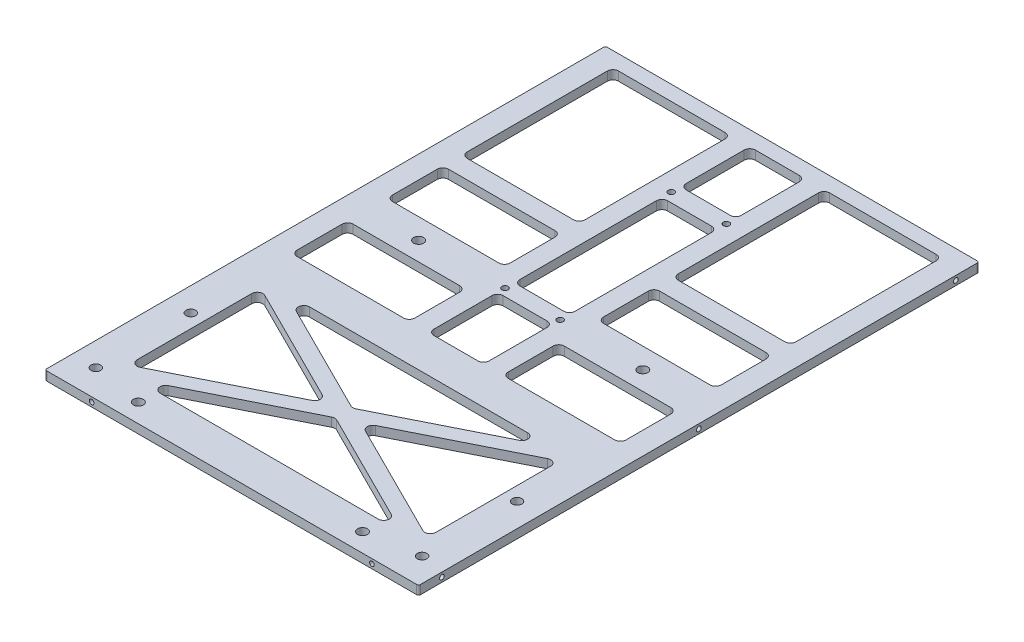
SolidWorks part; units mm, degrees
material "6061 Alloy"
ref_plane "Front Plane" through (0, 0, 0) normal (0, 0, 1) x (1, 0, 0)
ref_plane "Top Plane" through (0, 0, 0) normal (0, 1, 0) x (1, 0, 0)
ref_plane "Right Plane" through (0, 0, 0) normal (1, 0, 0) x (0, 0, -1)
sketch "Sketch1" plane through (0, 0, 0) normal (0, 1, 0) x (1, 0, 0)
  line L1 (-100, -150) -> (100, -150)
  line L2 (-100, -150) -> (-100, 150)
  line L3 (-100, 150) -> (100, 150)
  line L4 (100, -150) -> (100, 150)
  line L5 (-100, -150) -> (100, 150) construction
  line L6 (-100, 150) -> (100, -150) construction
  point P0 (0, 0)
  dimension "D1" = 300
  dimension "D2" = 200
extrude "Boss-Extrude1" add sketch "Sketch1" along normal blind 4.7625
sketch "Sketch2" plane through (0, 4.7625, 0) normal (0, 1, 0) x (1, 0, 0)
  line L0 (100, -150) -> (100, 150) construction
  line L1 (-100, -122.7) -> (100, -122.7) construction
  line L2 (-100, -122.7) -> (-100, -97.3) construction
  line L3 (-100, -97.3) -> (100, -97.3) construction
  line L4 (100, -122.7) -> (100, -97.3) construction
  line L5 (-100, -122.7) -> (100, -97.3) construction
  line L6 (-100, -97.3) -> (100, -122.7) construction
  line L7 (-100, -150) -> (100, -150) construction
  line L8 (100, 150) -> (-100, 150) construction
  line L9 (-100, -97.3) -> (-87.3, -97.3) construction
  line L10 (-100, -97.3) -> (-100, -84.6) construction
  line L11 (-100, -84.6) -> (-87.3, -84.6) construction
  line L12 (-87.3, -97.3) -> (-87.3, -84.6) construction
  line L13 (100, -97.3) -> (87.3, -97.3) construction
  line L14 (100, -97.3) -> (100, -84.6) construction
  line L15 (100, -84.6) -> (87.3, -84.6) construction
  line L16 (87.3, -97.3) -> (87.3, -84.6) construction
  line L17 (100, -122.7) -> (87.3, -122.7) construction
  line L18 (100, -122.7) -> (100, -135.4) construction
  line L19 (100, -135.4) -> (87.3, -135.4) construction
  line L20 (87.3, -122.7) -> (87.3, -135.4) construction
  line L21 (-100, -122.7) -> (-87.3, -122.7) construction
  line L22 (-100, -122.7) -> (-100, -135.4) construction
  line L23 (-100, -135.4) -> (-87.3, -135.4) construction
  line L24 (-87.3, -122.7) -> (-87.3, -135.4) construction
  line L25 (-100, -110) -> (100, -110) construction
  line L28 (-60, -140) -> (60, -140) construction
  line L29 (-60, -140) -> (-60, 10) construction
  line L30 (-60, 10) -> (60, 10) construction
  line L31 (60, -140) -> (60, 10) construction
  line L32 (-60, -140) -> (60, 10) construction
  line L33 (-60, 10) -> (60, -140) construction
  line L34 (-14.75, 11) -> (14.75, 11) construction
  line L35 (-14.75, 11) -> (-14.75, 100) construction
  line L36 (-14.75, 100) -> (14.75, 100) construction
  line L37 (14.75, 11) -> (14.75, 100) construction
  line L38 (-14.75, 11) -> (14.75, 100) construction
  line L39 (-14.75, 100) -> (14.75, 11) construction
  line L40 (-12.5, -79) -> (12.5, -79) construction
  line L41 (-12.5, -79) -> (-12.5, -4) construction
  line L42 (-12.5, -4) -> (12.5, -4) construction
  line L43 (12.5, -79) -> (12.5, -4) construction
  line L44 (-12.5, -79) -> (12.5, -4) construction
  line L45 (-12.5, -4) -> (12.5, -79) construction
  point P0 (0, -110)
  point P24 (0, 55.5)
  point P26 (0, -110)
  point P32 (0, -41.5)
  point P123 (0, -65)
  dimension "D1" = 25.4
  dimension "D2" = 40
  dimension "D3" = 12.7
  dimension "D4" = 12.7
  dimension "D5" = 120
  dimension "D6" = 150
  dimension "D7" = 10
  dimension "D8" = 75
  dimension "D9" = 89
  dimension "D10" = 29.5
  dimension "D11" = 50
  dimension "D12" = 25
  dimension "D13" = 15
hole_wizard "1/4-20 Tapped Hole1" positions "Sketch4" profile "Sketch5" tap size "1/4-20" standard "ANSI Inch" end condition through all
sketch "Sketch4" plane through (0, 4.7625, 0) normal (0, 1, 0) x (1, 0, 0)
  point P0 (-87.3, -84.6)
  point P3 (-87.3, -135.4)
  point P6 (87.3, -135.4)
  point P9 (87.3, -84.6)
sketch "Sketch5" plane through (-87.3, 4.7625, 84.6) normal (1, 0, 0) x (0, 0, 1)
  line L0 (0, 0) -> (0, 4.7625)
  line L1 (0, 4.7625) -> (2.5527, 4.7625)
  line L2 (2.5527, 4.7625) -> (2.5527, 0)
  line L5 (2.5527, 0) -> (0, 0)
  line L11 (0, -6.35) -> (0, 107.95) construction
  dimension "Thru Tap Drill Dia." = 5.1054
  dimension "Thru Tap Drill Depth" = 4.7625
ref_plane "Plane1" through (0, 0, 110) normal (0, 0, 1) x (1, 0, 0)
hole_wizard "M4x0.7 Tapped Hole1" positions "Sketch16" profile "Sketch17" tap size "M4x0.7" standard "ANSI Metric" end condition through all
sketch "Sketch16" plane through (0, 4.7625, 0) normal (0, 1, 0) x (1, 0, 0)
  point P12 (-14.75, 11)
  point P15 (14.75, 11)
  point P18 (14.75, 100)
  point P21 (-14.75, 100)
sketch "Sketch17" plane through (-14.75, 4.7625, -11) normal (1, 0, 0) x (0, 0, 1)
  line L0 (0, 0) -> (0, 4.7625)
  line L1 (0, 4.7625) -> (1.65, 4.7625)
  line L2 (1.65, 4.7625) -> (1.65, 0)
  line L5 (1.65, 0) -> (0, 0)
  line L11 (0, -6.35) -> (0, 107.95) construction
  dimension "Thru Tap Drill Dia." = 3.3
  dimension "Thru Tap Drill Depth" = 4.7625
cosmetic thread "Hole Thread1" parameters "D2"=4
cosmetic thread "Hole Thread2" parameters "D2"=4
cosmetic thread "Hole Thread3" parameters "D2"=4
cosmetic thread "Hole Thread4" parameters "D2"=4
hole_wizard "M5 Clearance Hole1" positions "Sketch7" profile "Sketch8" hole size "M5" standard "ANSI Metric" end condition through all
sketch "Sketch7" plane through (0, 4.7625, 0) normal (0, 1, 0) x (1, 0, 0)
  point P0 (-60, 10)
  point P3 (-60, -140)
  point P6 (60, -140)
  point P9 (60, 10)
sketch "Sketch8" plane through (-60, 4.7625, -10) normal (1, 0, 0) x (0, 0, 1)
  line L0 (0, 0) -> (0, 4.7625)
  line L1 (0, 4.7625) -> (2.65, 4.7625)
  line L2 (2.65, 4.7625) -> (2.65, 0)
  line L5 (2.65, 0) -> (0, 0)
  line L11 (0, -6.35) -> (0, 107.95) construction
  dimension "Thru Hole Dia." = 5.3
  dimension "Thru Hole Depth" = 4.7625
sketch "Sketch9" plane through (0, 4.7625, 0) normal (0, 1, 0) x (1, 0, 0)
  line L23 (-81.7889, -53.5777) -> (78.2111, -133.5777) construction
  line L24 (-80, -130) -> (80, -130) construction
  line L25 (-80, -130) -> (-80, -50) construction
  line L26 (-80, -50) -> (80, -50) construction
  line L27 (80, -130) -> (80, -50) construction
  line L28 (-80, -130) -> (80, -50) construction
  line L29 (-80, -50) -> (80, -130) construction
  line L30 (-78.2111, -46.4223) -> (81.7889, -126.4223) construction
  line L31 (-78.2111, -133.5777) -> (81.7889, -53.5777) construction
  line L32 (-81.7889, -126.4223) -> (78.2111, -46.4223) construction
  line L33 (-80, -54.4721) -> (-80, -125.5279)
  line L34 (-80, -125.5279) -> (-8.9443, -90)
  line L35 (-8.9443, -90) -> (-80, -54.4721)
  line L36 (-71.0557, -50) -> (71.0557, -50)
  line L37 (71.0557, -50) -> (0, -85.5279)
  line L38 (0, -85.5279) -> (-71.0557, -50)
  line L39 (80, -54.4721) -> (8.9443, -90)
  line L40 (8.9443, -90) -> (80, -125.5279)
  line L41 (80, -125.5279) -> (80, -54.4721)
  line L42 (-71.0557, -130) -> (0, -94.4721)
  line L43 (0, -94.4721) -> (71.0557, -130)
  line L44 (71.0557, -130) -> (-71.0557, -130)
  line L45 (-100, -150) -> (100, -150) construction
  line L47 (-88, -30) -> (-25, -30) construction
  line L48 (-88, -30) -> (-88, 142) construction
  line L49 (-88, 142) -> (-25, 142)
  line L50 (-25, -30) -> (-25, 142) construction
  line L51 (-88, -30) -> (-25, 142) construction
  line L52 (-88, 142) -> (-25, -30) construction
  line L54 (25, -30) -> (88, -30) construction
  line L55 (25, -30) -> (25, 142) construction
  line L56 (25, 142) -> (88, 142)
  line L57 (88, -30) -> (88, 142) construction
  line L58 (25, -30) -> (88, 142) construction
  line L59 (25, 142) -> (88, -30) construction
  line L60 (-56.5, 56) -> (56.5, 56) construction
  line L62 (100, 150) -> (-100, 150) construction
  line L63 (-100, 150) -> (-100, -150) construction
  line L65 (-14.75, 16) -> (14.75, 16)
  line L66 (-14.75, 16) -> (-14.75, 95)
  line L67 (-14.75, 95) -> (14.75, 95)
  line L68 (14.75, 16) -> (14.75, 95)
  line L69 (-14.75, 16) -> (14.75, 95) construction
  line L70 (-14.75, 95) -> (14.75, 16) construction
  line L71 (-14.75, 100) -> (14.75, 11) construction
  line L72 (14.75, 11) -> (14.75, 100) construction
  line L81 (-12.5, -79) -> (12.5, -4) construction
  line L84 (-14.75, 100) -> (14.75, 100) construction
  line L86 (-88, 51) -> (-25, 51) construction
  line L87 (-88, 51) -> (-88, 61) construction
  line L88 (-88, 61) -> (-25, 61)
  line L89 (-25, 51) -> (-25, 61) construction
  line L90 (-88, 51) -> (-25, 61) construction
  line L91 (-88, 61) -> (-25, 51) construction
  line L93 (25, 51) -> (88, 51) construction
  line L94 (25, 51) -> (25, 61) construction
  line L95 (25, 61) -> (88, 61)
  line L96 (88, 51) -> (88, 61) construction
  line L97 (25, 51) -> (88, 61) construction
  line L98 (25, 61) -> (88, 51) construction
  line L99 (-88, 61) -> (-88, 142)
  line L101 (-25, 142) -> (-25, 61)
  line L103 (-88, 51) -> (-88, -30) construction
  line L105 (-25, -30) -> (-25, 51) construction
  line L107 (25, 51) -> (25, -30) construction
  line L109 (88, -30) -> (88, 51) construction
  line L111 (88, 61) -> (88, 142)
  line L113 (25, 142) -> (25, 61)
  line L115 (-14.75, 105) -> (14.75, 105)
  line L116 (-14.75, 105) -> (-14.75, 142)
  line L117 (-14.75, 142) -> (14.75, 142)
  line L118 (14.75, 105) -> (14.75, 142)
  line L119 (-14.75, 105) -> (14.75, 142) construction
  line L120 (-14.75, 142) -> (14.75, 105) construction
  line L121 (-14.75, -30) -> (14.75, -30)
  line L122 (-14.75, -30) -> (-14.75, 7)
  line L123 (-14.75, 7) -> (14.75, 7)
  line L124 (14.75, -30) -> (14.75, 7)
  line L125 (-14.75, -30) -> (14.75, 7) construction
  line L126 (-14.75, 7) -> (14.75, -30) construction
  line L127 (-88, 21) -> (-25, 21)
  line L128 (-88, 21) -> (-88, 51)
  line L129 (-88, 51) -> (-25, 51)
  line L130 (-25, 21) -> (-25, 51)
  line L131 (-88, 21) -> (-25, 51) construction
  line L132 (-88, 51) -> (-25, 21) construction
  line L133 (-88, -30) -> (-25, -30)
  line L134 (-88, -30) -> (-88, 0)
  line L135 (-88, 0) -> (-25, 0)
  line L136 (-25, -30) -> (-25, 0)
  line L137 (25, -30) -> (88, -30)
  line L138 (25, -30) -> (25, 0)
  line L139 (25, 0) -> (88, 0)
  line L140 (88, -30) -> (88, 0)
  line L141 (88, 51) -> (25, 51)
  line L142 (88, 51) -> (88, 21)
  line L143 (88, 21) -> (25, 21)
  line L144 (25, 51) -> (25, 21)
  point P0 (-56.5, 56)
  point P5 (56.5, 56)
  point P13 (0, 56)
  point P18 (0, 55.5)
  point P27 (0, -90)
  point P28 (0, -41.5)
  point P35 (0, 123.5)
  point P62 (0, -11.5)
  point P77 (-56.5, 36)
  dimension "D2" = 8
  dimension "D3" = 12
  dimension "D6" = 160
  dimension "D7" = 80
  dimension "D12" = 20
  dimension "D13" = 10
  dimension "D4" = 20
  dimension "D5" = 50
  dimension "D14" = 5
  dimension "D15" = 10
  dimension "D16" = 30
  dimension "D17" = 30
  dimension "D8" = 4
  dimension "D9" = 4
  dimension "D10" = 4
  dimension "D11" = 4
extrude "Cut-Extrude1" cut sketch "Sketch9" against normal through all
sketch "Sketch10" plane through (0, 0, 150) normal (0, 0, 1) x (1, 0, 0)
  line L0 (-75, 2.3813) -> (75, 2.3813) construction
  line L1 (-100, 4.7625) -> (-100, 0) construction
  point P3 (0, 2.3813)
  point P7 (-100, 2.3813)
  dimension "D1" = 150
hole_wizard "Tap Drill for M3x0.5 Tap1" positions "Sketch11" profile "Sketch12" hole size "M3x0.5" standard "ANSI Metric"
sketch "Sketch11" plane through (0, 0, 150) normal (0, 0, 1) x (1, 0, 0)
  point P0 (-75, 2.3813)
  point P3 (75, 2.3813)
sketch "Sketch12" plane through (-75, 2.3813, 150) normal (1, 0, 0) x (0, -1, 0)
  line L0 (0, 0) -> (0, 5.5111)
  line L1 (0, 5.5111) -> (1.25, 4.76)
  line L2 (1.25, 4.76) -> (1.25, 0)
  line L5 (1.25, 0) -> (0, 0)
  line L10 (0, 5.5111) -> (-1.25, 4.76) construction
  line L11 (0, -6.35) -> (0, 107.95) construction
  dimension "Hole Dia." = 2.5
  dimension "Hole Depth" = 4.76
  dimension "Drill Angle" = 118
mirror "Mirror1" about plane through (0, 0, 0) normal (0, 0, 1) of "Tap Drill for M3x0.5 Tap1"
sketch "Sketch13" plane through (-100, 0, 0) normal (-1, 0, 0) x (0, 0, 1)
  line L0 (137.5, 2.3813) -> (-137.5, 2.3813) construction
  line L1 (-150, 4.7625) -> (-150, 0) construction
  point P3 (0, 2.3812)
  point P7 (-150, 2.3813)
  dimension "D1" = 275
hole_wizard "Tap Drill for M3x0.5 Tap2" positions "Sketch14" profile "Sketch15" hole size "M3x0.5" standard "ANSI Metric"
sketch "Sketch14" plane through (-100, 0, 0) normal (-1, 0, 0) x (0, 0, 1)
  point P0 (-137.5, 2.3813)
  point P3 (137.5, 2.3813)
  point P6 (0, 2.3812)
sketch "Sketch15" plane through (-100, 2.3813, -137.5) normal (0, 1, 0) x (0, 0, 1)
  line L0 (0, 0) -> (0, 5.5111)
  line L1 (0, 5.5111) -> (1.25, 4.76)
  line L2 (1.25, 4.76) -> (1.25, 0)
  line L5 (1.25, 0) -> (0, 0)
  line L10 (0, 5.5111) -> (-1.25, 4.76) construction
  line L11 (0, -6.35) -> (0, 107.95) construction
  dimension "Hole Dia." = 2.5
  dimension "Hole Depth" = 4.76
  dimension "Drill Angle" = 118
mirror "Mirror2" about plane through (0, 0, 0) normal (1, 0, 0) of "Tap Drill for M3x0.5 Tap2"
fillet "Fillet1" radius 3 48 edges at (-71.0557, 2.3813, 130) (71.0557, 2.3813, 130) (0, 2.3813, 94.4721) (80, 2.3813, 125.5279) (80, 2.3813, 54.4721) (8.9443, 2.3813, 90) (71.0557, 2.3813, 50) (0, 2.3813, 85.5279) (-71.0557, 2.3813, 50) (-8.9443, 2.3813, 90) (-80, 2.3813, 125.5279) (-80, 2.3813, 54.4721) (14.75, 2.3813, -16) (-14.75, 2.3813, -95) (14.75, 2.3813, -95) (-14.75, 2.3813, -16) (88, 2.3813, -61) (25, 2.3813, -142) (88, 2.3813, -142) (25, 2.3813, -61) (-25, 2.3813, -61) (-88, 2.3813, -142) (-25, 2.3813, -142) (-88, 2.3813, -61) (-14.75, 2.3813, -7) (14.75, 2.3813, -7) (14.75, 2.3813, 30) (-14.75, 2.3813, 30) (14.75, 2.3813, -105) (-14.75, 2.3813, -142) (14.75, 2.3813, -142) (-14.75, 2.3813, -105) (-25, 2.3813, -21) (-88, 2.3813, -51) (-25, 2.3813, -51) (25, 2.3813, -51) (88, 2.3813, -51) (88, 2.3813, -21) (25, 2.3813, -21) (-88, 2.3813, 0) (-25, 2.3813, 0) (-25, 2.3813, 30) (-88, 2.3813, 30) (25, 2.3813, 0) (88, 2.3813, 0) (88, 2.3813, 30) (25, 2.3813, 30) (-88, 2.3813, -21)
fillet "Fillet2" radius 1 4 edges at (100, 2.3813, 150) (-100, 2.3813, 150) (-100, 2.3813, -150) (100, 2.3813, -150)
